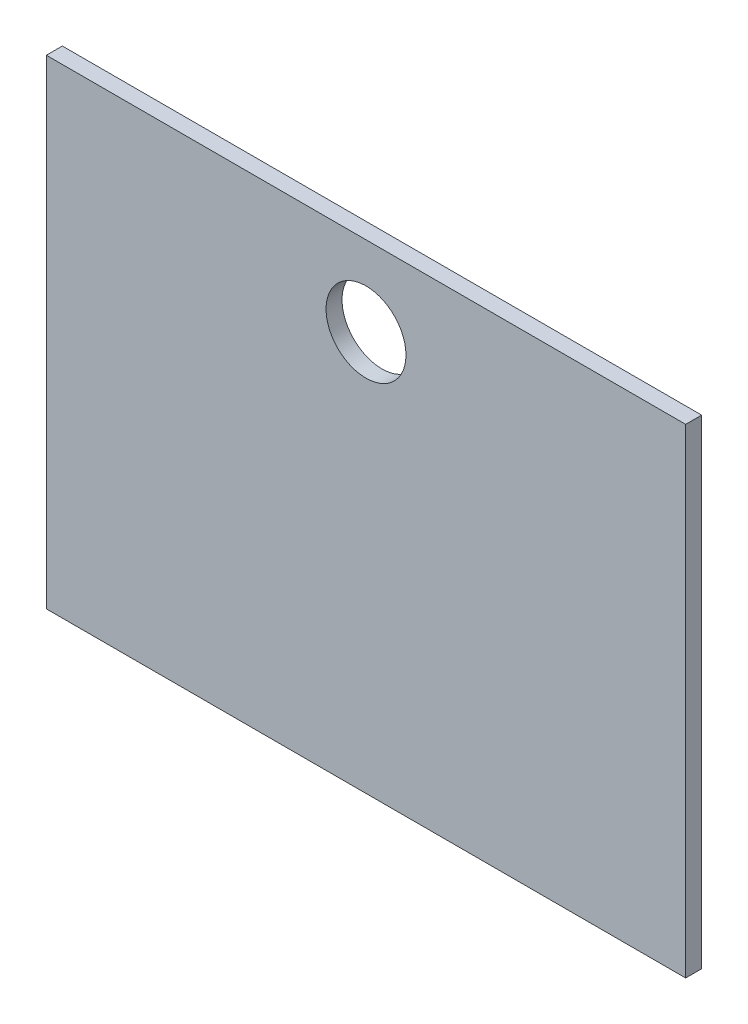
SolidWorks part; units mm, degrees
ref_plane "Спереди" through (0, 0, 0) normal (0, 0, 1) x (1, 0, 0)
ref_plane "Сверху" through (0, 0, 0) normal (0, 1, 0) x (1, 0, 0)
ref_plane "Справа" through (0, 0, 0) normal (1, 0, 0) x (0, 0, -1)
other "Configuration Table"
sketch "Эскиз1" plane through (0, 0, 0) normal (0, 0, 1) x (1, 0, 0)
  line L1 (40, 10) -> (-40, 10)
  line L2 (40, 10) -> (40, -10)
  line L3 (40, -10) -> (-40, -10)
  line L4 (-40, 10) -> (-40, -10)
  line L5 (40, 10) -> (-40, -10) construction
  line L6 (40, -10) -> (-40, 10) construction
  point P0 (0, 0)
  dimension "D1" = 80
  dimension "D2" = 20
extrude "Бобышка-Вытянуть1" add sketch "Эскиз1" along normal blind 2
sketch "Эскиз2" plane through (0, 0, 2) normal (0, 0, 1) x (1, 0, 0)
  circle A0 centre (0, 0) radius 5
  dimension "D1" = 10
extrude "Вырез-Вытянуть1" cut sketch "Эскиз2" against normal through all
sketch "Эскиз3" plane through (0, -10, 0) normal (0, -1, 0) x (1, 0, 0)
  line L1 (-40, 2) -> (40, 2)
  line L2 (-40, 2) -> (-40, 0)
  line L3 (-40, 0) -> (40, 0)
  line L4 (40, 2) -> (40, 0)
  line L6 (40, 2) -> (40, 0) construction
  line L7 (-40, 0) -> (40, 0) construction
  dimension "D1" = 2
  dimension "D2" = 80
extrude "Бобышка-Вытянуть2" add sketch "Эскиз3" along normal blind 40
